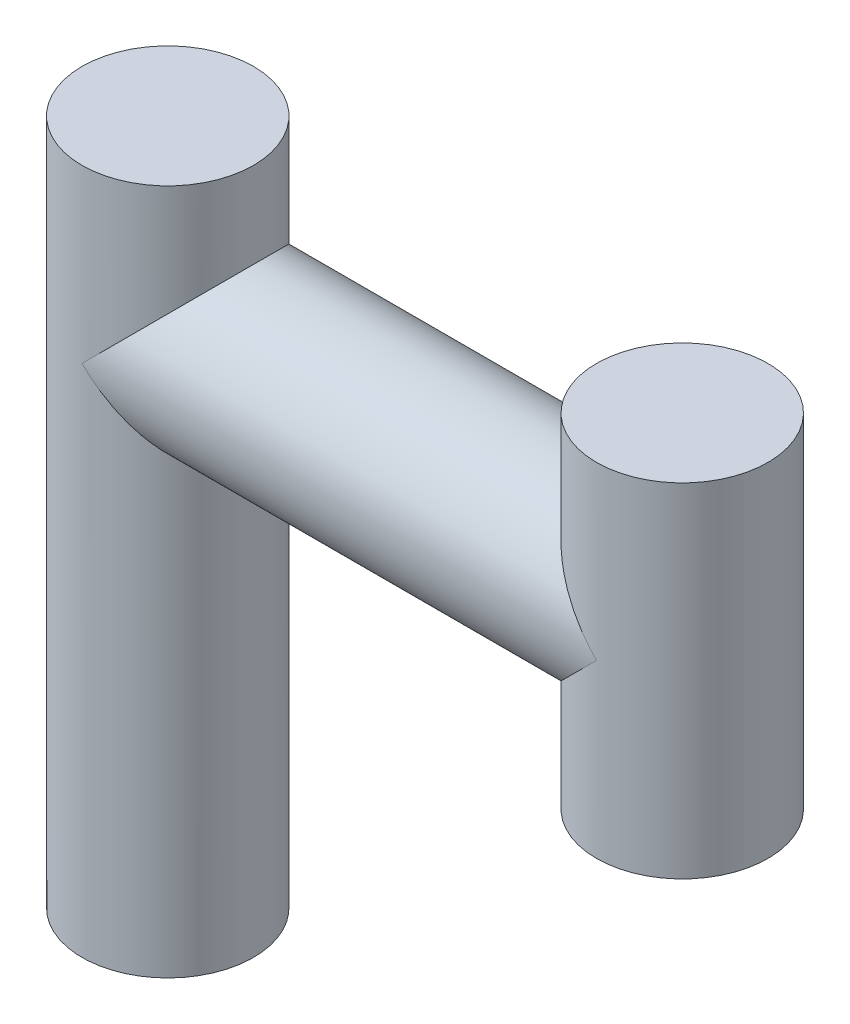
SolidWorks part; units mm, degrees
ref_plane "Front Plane" through (0, 0, 0) normal (0, 0, 1) x (1, 0, 0)
ref_plane "Top Plane" through (0, 0, 0) normal (0, 1, 0) x (1, 0, 0)
ref_plane "Right Plane" through (0, 0, 0) normal (1, 0, 0) x (0, 0, -1)
sketch "Sketch2" plane through (0, 0, 0) normal (0, 1, 0) x (1, 0, 0)
  circle A0 centre (0, 0) radius 2.5
  dimension "D1" = 5
extrude "Boss-Extrude2" add sketch "Sketch2" along normal blind 10
sketch "Sketch3" plane through (0, 0, 0) normal (1, 0, 0) x (0, 0, -1)
  line L0 (0, 0) -> (0, 10) construction
  line L1 (2.5, 10) -> (-2.5, 10) construction
  line L2 (-2.5, 5) -> (2.5, 5) construction
  line L3 (-2.5, 10) -> (-2.5, 0) construction
  line L4 (2.5, 0) -> (2.5, 10) construction
  circle A0 centre (0, 5) radius 2.5
  dimension "D1" = 5
extrude "Boss-Extrude3" add sketch "Sketch3" along normal blind 7.5
mirror "Mirror5" about plane through (7.5, 5, 0) normal (1, 0, 0) of "Boss-Extrude2", "Boss-Extrude3"
sketch "Sketch4" plane through (0, 0, 0) normal (0, -1, 0) x (1, 0, 0)
  circle A0 centre (0, 0) radius 2.5 construction
  circle A1 centre (0, 0) radius 2.5
extrude "Boss-Extrude4" add sketch "Sketch4" along normal blind 10
